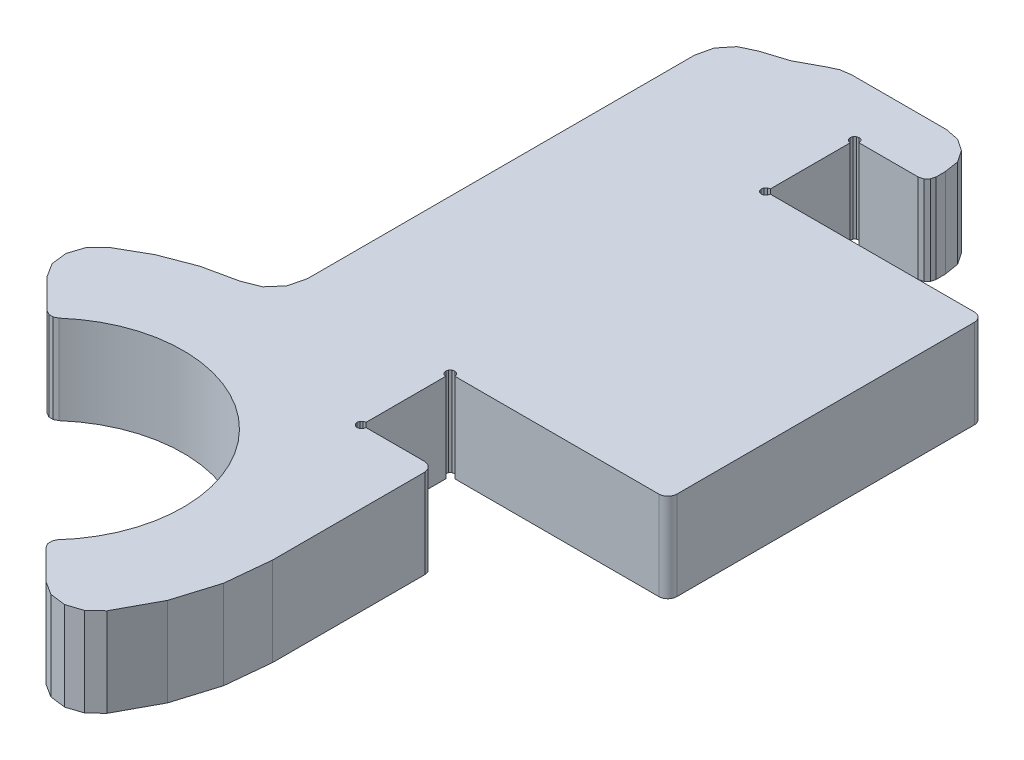
SolidWorks part; units mm, degrees
ref_plane "Plan de face" through (0, 0, 0) normal (0, 0, 1) x (1, 0, 0)
ref_plane "Plan de dessus" through (0, 0, 0) normal (0, 1, 0) x (1, 0, 0)
ref_plane "Plan de droite" through (0, 0, 0) normal (1, 0, 0) x (0, 0, -1)
ref_plane "Plan1" through (0, 4.9, 0) normal (0, 1, 0) x (1, 0, 0)
sketch "Esquisse1" plane through (0, 4.9, 0) normal (0, 1, 0) x (1, 0, 0)
  line L0 (20.3521, -2.5435) -> (20.3521, -2.0435)
  line L1 (20.3521, -2.0435) -> (20.2222, -1.2346)
  line L2 (20.2222, -1.2346) -> (19.7887, -0.5858)
  line L3 (19.7887, -0.5858) -> (19.1398, -0.1522)
  line L4 (19.1398, -0.1522) -> (18.3745, 0)
  line L5 (18.3745, 0) -> (13.1508, 0)
  line L6 (13.1508, 0) -> (12.5705, -0.0861)
  line L7 (12.5705, -0.0861) -> (12.04, -0.3368)
  line L8 (12.04, -0.3368) -> (10.7985, -1.0065)
  line L9 (10.7985, -1.0065) -> (9.4534, -1.4319)
  line L10 (9.4534, -1.4319) -> (8.6403, -1.8133)
  line L11 (8.6403, -1.8133) -> (8.0761, -2.512)
  line L12 (8.0761, -2.512) -> (7.8745, -3.3871)
  line L13 (7.8745, -3.3871) -> (7.8745, -24.7386)
  line L14 (7.8745, -24.7386) -> (7.6508, -25.6577)
  line L15 (7.6508, -25.6577) -> (7.0298, -26.3712)
  line L16 (7.0298, -26.3712) -> (6.1503, -26.7195)
  line L17 (6.1503, -26.7195) -> (4.2981, -27.1225)
  line L18 (4.2981, -27.1225) -> (2.5281, -27.8011)
  line L19 (2.5281, -27.8011) -> (0.8811, -28.7394)
  line L20 (0.8811, -28.7394) -> (0.2809, -29.375)
  line L21 (0.2809, -29.375) -> (0.0092, -30.2057)
  line L22 (0.0092, -30.2057) -> (0.1177, -31.0731)
  line L23 (0.1177, -31.0731) -> (0.5858, -31.8113)
  line L24 (0.5858, -31.8113) -> (2.2287, -33.4542)
  line L25 (2.2287, -33.4542) -> (2.4428, -33.5808)
  line L26 (2.4428, -33.5808) -> (2.6914, -33.5886)
  line L27 (2.6914, -33.5886) -> (2.913, -33.4756)
  line L40 (13.4306, -44.1378) -> (13.3636, -44.3265)
  line L41 (13.3636, -44.3265) -> (13.3713, -44.5752)
  line L42 (13.3713, -44.5752) -> (13.4979, -44.7893)
  line L43 (13.4979, -44.7893) -> (15.1408, -46.4322)
  line L44 (15.1408, -46.4322) -> (15.8791, -46.9002)
  line L45 (15.8791, -46.9002) -> (16.7464, -47.0088)
  line L46 (16.7464, -47.0088) -> (17.5772, -46.737)
  line L47 (17.5772, -46.737) -> (18.2127, -46.1369)
  line L48 (18.2127, -46.1369) -> (19.3856, -43.9632)
  line L49 (19.3856, -43.9632) -> (20.1081, -41.6013)
  line L50 (20.1081, -41.6013) -> (20.3521, -39.1435)
  line L51 (20.3521, -39.1435) -> (20.3521, -30.7435)
  line L52 (20.3521, -30.7435) -> (20.2852, -30.4935)
  line L53 (20.2852, -30.4935) -> (20.1021, -30.3105)
  line L54 (20.1021, -30.3105) -> (19.8521, -30.2435)
  line L55 (19.8521, -30.2435) -> (16.6021, -30.2435)
  line L56 (16.6021, -30.2435) -> (16.5686, -30.3685)
  line L57 (16.5686, -30.3685) -> (16.4771, -30.46)
  line L58 (16.4771, -30.46) -> (16.3521, -30.4935)
  line L59 (16.3521, -30.4935) -> (16.2271, -30.46)
  line L60 (16.2271, -30.46) -> (16.1356, -30.3685)
  line L61 (16.1356, -30.3685) -> (16.1021, -30.2435)
  line L62 (16.1021, -30.2435) -> (16.1356, -30.1185)
  line L63 (16.1356, -30.1185) -> (16.2271, -30.027)
  line L64 (16.2271, -30.027) -> (16.3521, -29.9935)
  line L65 (16.3521, -29.9935) -> (16.3521, -25.5935)
  line L66 (16.3521, -25.5935) -> (16.2271, -25.56)
  line L67 (16.2271, -25.56) -> (16.1356, -25.4685)
  line L68 (16.1356, -25.4685) -> (16.1021, -25.3435)
  line L69 (16.1021, -25.3435) -> (16.1356, -25.2185)
  line L70 (16.1356, -25.2185) -> (16.2271, -25.127)
  line L71 (16.2271, -25.127) -> (16.3521, -25.0935)
  line L72 (16.3521, -25.0935) -> (16.4771, -25.127)
  line L73 (16.4771, -25.127) -> (16.5686, -25.2185)
  line L74 (16.5686, -25.2185) -> (16.6021, -25.3435)
  line L75 (16.6021, -25.3435) -> (27.8521, -25.3435)
  line L79 (28.3521, -24.8435) -> (28.3521, -8.4435)
  line L83 (27.8521, -7.9435) -> (16.6021, -7.9435)
  line L84 (16.6021, -7.9435) -> (16.5686, -8.0685)
  line L85 (16.5686, -8.0685) -> (16.4771, -8.16)
  line L86 (16.4771, -8.16) -> (16.3521, -8.1935)
  line L87 (16.3521, -8.1935) -> (16.2271, -8.16)
  line L88 (16.2271, -8.16) -> (16.1356, -8.0685)
  line L89 (16.1356, -8.0685) -> (16.1021, -7.9435)
  line L90 (16.1021, -7.9435) -> (16.1356, -7.8185)
  line L91 (16.1356, -7.8185) -> (16.2271, -7.727)
  line L92 (16.2271, -7.727) -> (16.3521, -7.6935)
  line L93 (16.3521, -7.6935) -> (16.3521, -3.2935)
  line L94 (16.3521, -3.2935) -> (16.2271, -3.26)
  line L95 (16.2271, -3.26) -> (16.1356, -3.1685)
  line L96 (16.1356, -3.1685) -> (16.1021, -3.0435)
  line L97 (16.1021, -3.0435) -> (16.1356, -2.9185)
  line L98 (16.1356, -2.9185) -> (16.2271, -2.827)
  line L99 (16.2271, -2.827) -> (16.3521, -2.7935)
  line L100 (16.3521, -2.7935) -> (16.4771, -2.827)
  line L101 (16.4771, -2.827) -> (16.5686, -2.9185)
  line L102 (16.5686, -2.9185) -> (16.6021, -3.0435)
  line L103 (16.6021, -3.0435) -> (19.8521, -3.0435)
  line L104 (19.8521, -3.0435) -> (20.1021, -2.9765)
  line L105 (20.1021, -2.9765) -> (20.2852, -2.7935)
  line L106 (20.2852, -2.7935) -> (20.3521, -2.5435)
  arc A0 (13.4306, -44.1378) -> (2.913, -33.4756) centre (7.8745, -39.1) ccw
  arc A1 (27.8521, -7.9435) -> (28.3521, -8.4435) centre (27.8521, -8.4435) cw
  arc A2 (27.8521, -25.3435) -> (28.3521, -24.8435) centre (27.8521, -24.8435) ccw
  dimension "D1" = 15
  dimension "D4" = 8.8565
  dimension "D2" = 39.1
  dimension "D3" = 7.8745
  dimension "D5" = 4.9
  dimension "D6" = 17.4
  dimension "D7" = 4.9
  dimension "D8" = 16.3521
  dimension "D9" = 3.0435
extrude "Boss.-Extru.1" add sketch "Esquisse1" against normal blind 4.9
